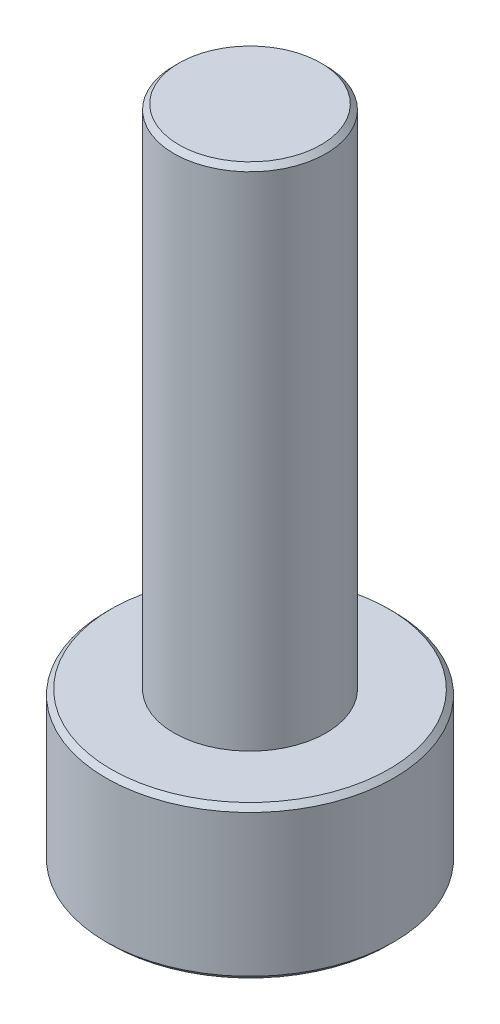
SolidWorks part; units mm, degrees
material "6061 合金"
ref_plane "前视基准面" through (0, 0, 0) normal (0, 0, 1) x (1, 0, 0)
ref_plane "上视基准面" through (0, 0, 0) normal (0, 1, 0) x (1, 0, 0)
ref_plane "右视基准面" through (0, 0, 0) normal (1, 0, 0) x (0, 0, -1)
sketch "草图1" plane through (0, 0, 0) normal (0, 1, 0) x (1, 0, 0)
  circle A0 centre (0, 0) radius 2.84
  dimension "D1" = 5.68
extrude "杯头部分" add sketch "草图1" along normal blind 3
sketch "草图2" plane through (0, 3, 0) normal (0, 1, 0) x (1, 0, 0)
  circle A0 centre (0, 0) radius 1.5
  dimension "D1" = 3
extrude "螺柱部分" add sketch "草图2" along normal blind 10
cosmetic thread "装饰螺纹线1" parameters "D2"=2.459
sketch "草图3" plane through (0, 0, 0) normal (0, -1, 0) x (1, 0, 0)
  line L1 (1.29, -0.7448) -> (1.29, 0.7448)
  line L2 (1.29, 0.7448) -> (0, 1.4896)
  line L3 (0, 1.4896) -> (-1.29, 0.7448)
  line L4 (-1.29, 0.7448) -> (-1.29, -0.7448)
  line L5 (-1.29, -0.7448) -> (0, -1.4896)
  line L6 (0, -1.4896) -> (1.29, -0.7448)
  circle A0 centre (0, 0) radius 1.29 construction
  dimension "D1" = 2.58
extrude "沉头内六角" cut sketch "草图3" against normal blind 1.3
chamfer "修饰性倒角" distance 0.1 angle 45 3 edges at (0, 13, 1.5) (0, 3, 2.84) (0, 0, 2.84)
